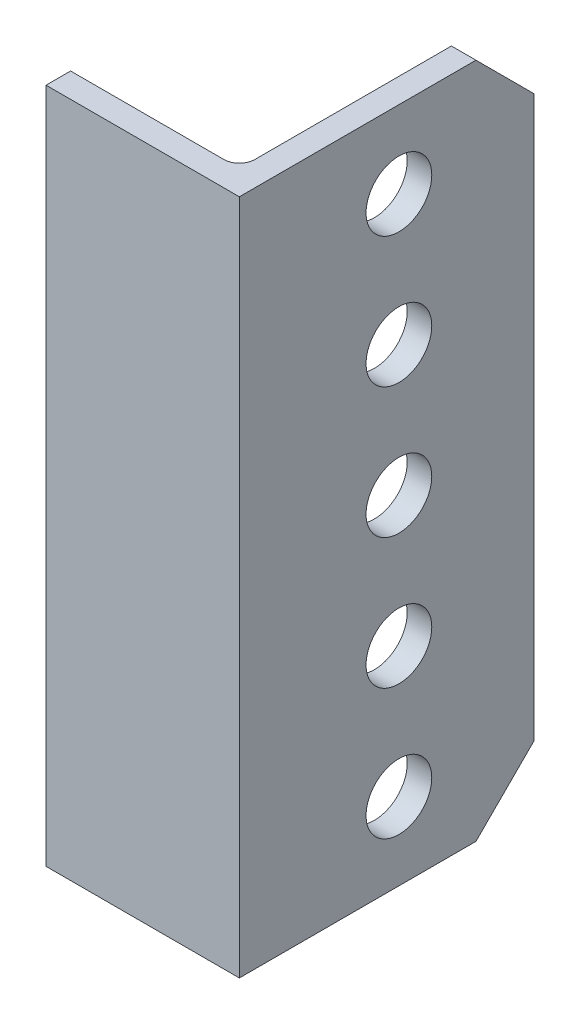
SolidWorks part; units mm, degrees
material "ASTM A36 Aço"
ref_plane "Plano frontal" through (0, 0, 0) normal (0, 0, 1) x (1, 0, 0)
ref_plane "Plano superior" through (0, 0, 0) normal (0, 1, 0) x (1, 0, 0)
ref_plane "Plano direito" through (0, 0, 0) normal (1, 0, 0) x (0, 0, -1)
sketch "Esboço1" plane through (0, 0, 0) normal (0, 1, 0) x (1, 0, 0)
  line L0 (-50, 0) -> (0, 0)
  line L1 (0, 0) -> (0, 76.2)
  line L2 (0, 76.2) -> (-2.35, 76.2)
  line L3 (-6.35, 72.2) -> (-6.35, 10.35)
  line L4 (-10.35, 6.35) -> (-50, 6.35)
  line L5 (-50, 6.35) -> (-50, 0)
  arc A0 (-6.35, 10.35) -> (-10.35, 6.35) centre (-10.35, 10.35) cw
  arc A1 (-2.35, 76.2) -> (-6.35, 72.2) centre (-2.35, 72.2) ccw
  point P11 (-6.35, 76.2)
  dimension "D4" = 4
  dimension "D1" = 50
  dimension "D2" = 76.2
  dimension "D3" = 6.35
  dimension "D5" = 6.35
extrude "Ressalto-extrusão1" add sketch "Esboço1" along normal mid plane 175
sketch "Esboço2" plane through (0, 0, 0) normal (1, 0, 0) x (0, 0, -1)
  line L0 (76.2, 0) -> (41.27, 0) construction
  line L1 (76.2, 87.5) -> (76.2, -87.5) construction
  line L2 (41.27, 0) -> (41.27, 33.75) construction
  line L3 (41.27, 33.75) -> (41.27, 67.5) construction
  line L4 (41.27, 0) -> (41.27, -33.75) construction
  line L5 (41.27, -33.75) -> (41.27, -67.5) construction
  line L6 (0, 87.5) -> (76.2, 87.5) construction
  line L7 (61.2, 87.5) -> (76.2, 87.5)
  line L8 (76.2, 87.5) -> (76.2, 72.5)
  line L9 (76.2, 72.5) -> (61.2, 87.5)
  line L10 (76.2, -72.5) -> (76.2, -87.5)
  line L11 (76.2, -87.5) -> (61.2, -87.5)
  line L12 (0, -87.5) -> (76.2, -87.5) construction
  line L13 (61.2, -87.5) -> (76.2, -72.5)
  circle A0 centre (41.27, 67.5) radius 8.5
  circle A1 centre (41.27, 33.75) radius 8.5
  circle A2 centre (41.27, 0) radius 8.5
  circle A3 centre (41.27, -33.75) radius 8.5
  circle A4 centre (41.27, -67.5) radius 8.5
  dimension "D1" = 17
  dimension "D2" = 34.93
  dimension "D3" = 33.75
  dimension "D4" = 15
extrude "Corte-extrusão1" cut sketch "Esboço2" against normal through all
